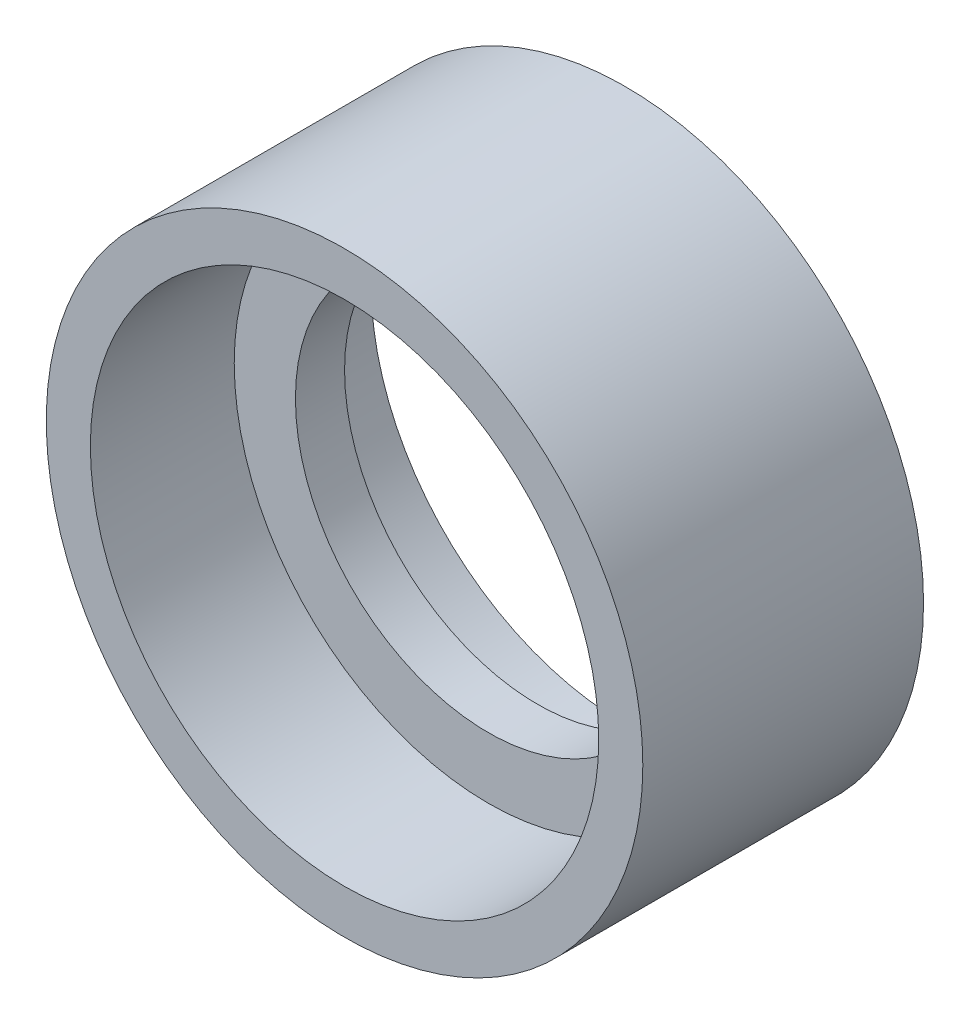
SolidWorks part; units mm, degrees
ref_plane "Front Plane" through (0, 0, 0) normal (0, 0, 1) x (1, 0, 0)
ref_plane "Top Plane" through (0, 0, 0) normal (0, 1, 0) x (1, 0, 0)
ref_plane "Right Plane" through (0, 0, 0) normal (1, 0, 0) x (0, 0, -1)
sketch "Sketch1" plane through (0, 0, 0) normal (0, 0, 1) x (1, 0, 0)
  circle A0 centre (0, 0) radius 13.4938
  dimension "D1" = 26.9875
extrude "Boss-Extrude1" add sketch "Sketch1" along normal blind 12.7
sketch "Sketch3" plane through (0, 0, 0) normal (0, 0, -1) x (-1, 0, 0)
  circle A0 centre (0, 0) radius 11.5
  dimension "D1" = 23
extrude "Cut-Extrude2" cut sketch "Sketch3" against normal through all
ref_plane "Plane1" through (0, 0, 3.9688) normal (0, 0, -1) x (-1, 0, 0)
sketch "Sketch4" plane through (0, 0, 3.9688) normal (0, 0, -1) x (-1, 0, 0)
  circle A1 centre (0, 0) radius 11.5
  dimension "D1" = 23
extrude "Boss-Extrude2" add sketch "Sketch4" against normal blind 2.2225
sketch "Sketch5" plane through (0, 0, 6.1913) normal (0, 0, 1) x (1, 0, 0)
  circle A0 centre (0, 0) radius 8.7312
  dimension "D1" = 17.4625
extrude "Cut-Extrude3" cut sketch "Sketch5" against normal through all
